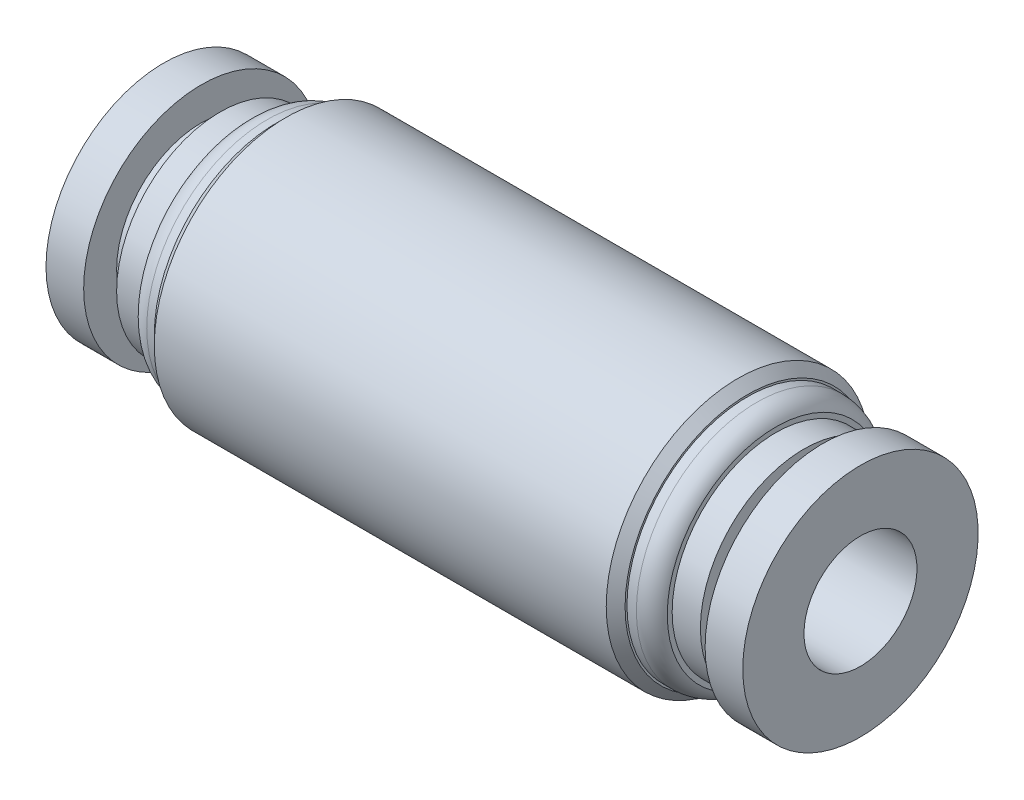
SolidWorks part; units mm, degrees
ref_plane "前视基准面" through (0, 0, 0) normal (0, 0, 1) x (1, 0, 0)
ref_plane "上视基准面" through (0, 0, 0) normal (0, 1, 0) x (1, 0, 0)
ref_plane "右视基准面" through (0, 0, 0) normal (1, 0, 0) x (0, 0, -1)
sketch "草图1" plane through (0, 0, 0) normal (0, 1, 0) x (1, 0, 0)
  line L0 (-37.3772, 0) -> (37.3772, 0) construction
  line L1 (0, 19.5482) -> (0, -19.5482) construction
  line L2 (-12.5, 7) -> (12.5, 7)
  line L3 (12.5, 7) -> (12.5, 6.4)
  line L4 (12.5, 6.4) -> (13, 6.4)
  line L5 (15.5, 5.5) -> (15.5, 4.5)
  line L6 (15.5, 4.5) -> (16.5, 4.5)
  line L7 (16.5, 4.5) -> (16.5, 6.25)
  line L8 (16.5, 6.25) -> (18.5, 6.25)
  line L9 (18.5, 6.25) -> (18.5, 3)
  line L10 (14, 5.7583) -> (14, 5.5)
  line L11 (14, 5.5) -> (15.5, 5.5)
  line L12 (-14, 5.5) -> (-15.5, 5.5)
  line L13 (-14, 5.7583) -> (-14, 5.5)
  line L14 (-18.5, 6.25) -> (-18.5, 3)
  line L15 (-16.5, 6.25) -> (-18.5, 6.25)
  line L16 (-16.5, 4.5) -> (-16.5, 6.25)
  line L17 (-15.5, 4.5) -> (-16.5, 4.5)
  line L18 (18.5, 3) -> (-18.5, 3)
  line L19 (-15.5, 5.5) -> (-15.5, 4.5)
  line L20 (-12.5, 6.4) -> (-13, 6.4)
  line L21 (-12.5, 7) -> (-12.5, 6.4)
  arc A0 (13, 6.4) -> (14, 5.7583) centre (13, 5.3) cw
  arc A1 (-13, 6.4) -> (-14, 5.7583) centre (-13, 5.3) ccw
  point P4 (0, 0)
  point P7 (0, 0)
  point P18 (0, 0)
  point P25 (0, 8)
  point P26 (0, 3)
  point P28 (0, 3)
  point P36 (0, 7)
  dimension "D4" = 1.5
  dimension "D12" = 1.1
  dimension "D1" = 14
  dimension "D2" = 25
  dimension "D3" = 1
  dimension "D5" = 2
  dimension "D6" = 12.5
  dimension "D7" = 1.5
  dimension "D8" = 1.5
  dimension "D9" = 6
  dimension "D10" = 0.5
  dimension "D11" = 0.6
  dimension "D13" = 1
  dimension "D14" = 37
revolve "旋转1" add sketch "草图1" angle 360 about L0
chamfer "倒角1" distance 0.5 angle 45 2 edges at (12.5, 0, 7) (-12.5, 0, 7)
